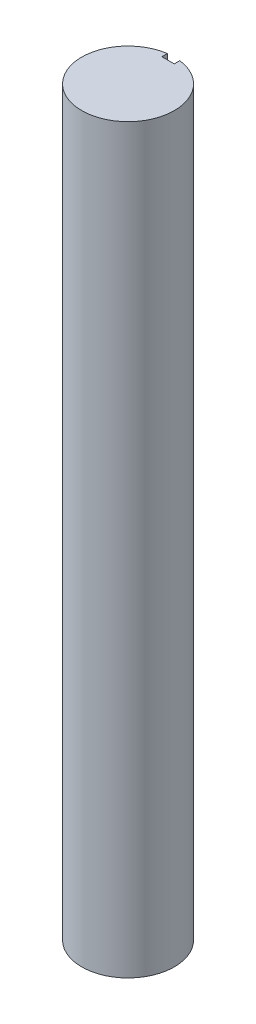
SolidWorks part; units mm, degrees
ref_plane "Front Plane" through (0, 0, 0) normal (0, 0, 1) x (1, 0, 0)
ref_plane "Top Plane" through (0, 0, 0) normal (0, 1, 0) x (1, 0, 0)
ref_plane "Right Plane" through (0, 0, 0) normal (1, 0, 0) x (0, 0, -1)
sketch "Sketch1" plane through (0, 0, 0) normal (0, 1, 0) x (1, 0, 0)
  line L2 (-0.9086, 6.2847) -> (-0.9086, 5.5348)
  line L3 (-0.9086, 5.5348) -> (0.7974, 5.5348)
  line L4 (0.7974, 6.2997) -> (0.7974, 5.5348)
  arc A0 (-0.9086, 6.2847) -> (0.7974, 6.2997) centre (0, 0) ccw
  dimension "D1" = 12.7
extrude "Boss-Extrude1" add sketch "Sketch1" along normal blind 101.6
